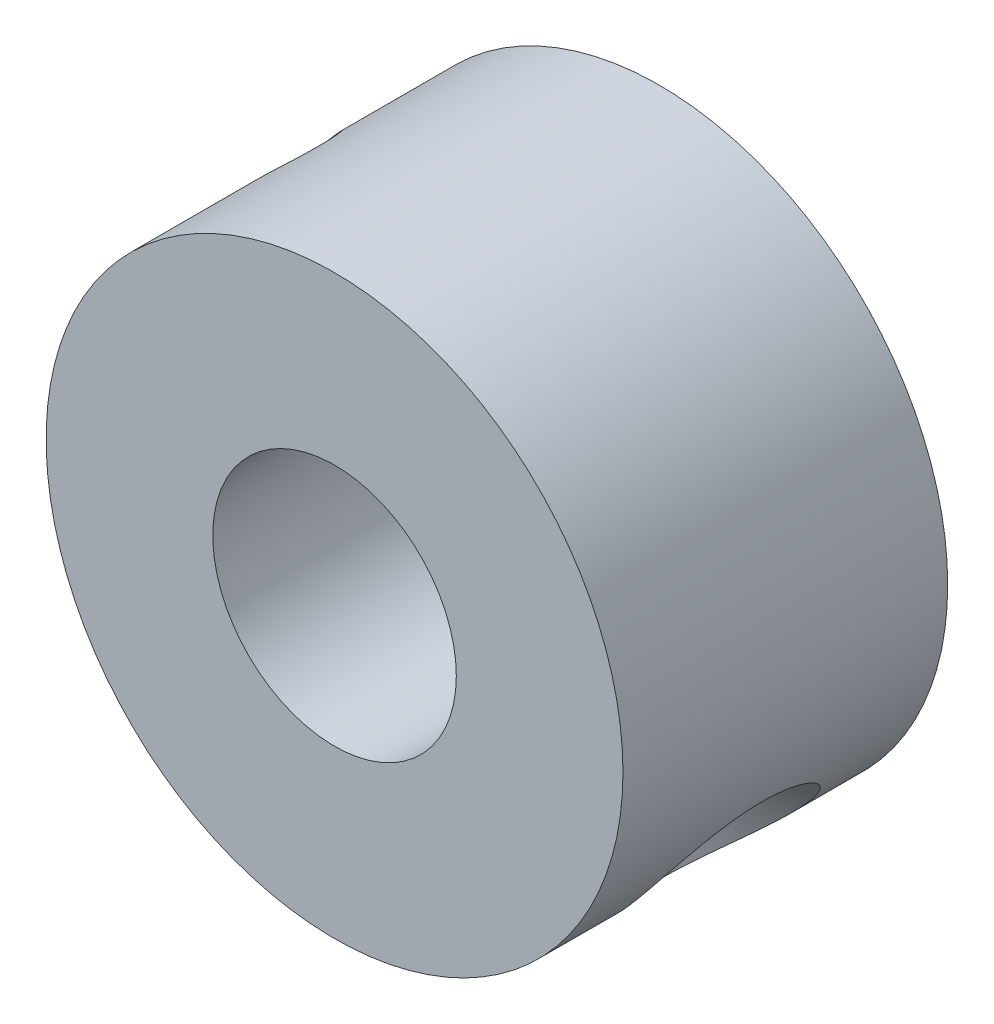
SolidWorks part; units mm, degrees
ref_plane "Front Plane" through (0, 0, 0) normal (0, 0, 1) x (1, 0, 0)
ref_plane "Top Plane" through (0, 0, 0) normal (0, 1, 0) x (1, 0, 0)
ref_plane "Right Plane" through (0, 0, 0) normal (1, 0, 0) x (0, 0, -1)
sketch "Sketch1" plane through (0, 0, 0) normal (0, 0, 1) x (1, 0, 0)
  circle A0 centre (0, 0) radius 7.1054
  circle A1 centre (0, 0) radius 3
extrude "Boss-Extrude3" add sketch "Sketch1" along normal blind 8 contours A1 | A0
sketch "Sketch2" plane through (0, 0, 8) normal (0, 0, 1) x (1, 0, 0)
  circle A0 centre (0, 0) radius 5
  circle A1 centre (0, 0) radius 3
hole_wizard "CSK for M2 Flat Head Machine Screw2" positions "3DSketch4" profile "Sketch6" countersink size "M2" standard "ANSI Metric" end condition through all
sketch3d "3DSketch4"
  point P0 (5.372, -4.6507, 3.8937)
sketch "Sketch6" plane through (5.372, -4.6507, 3.8937) normal (0, 0, 1) x (0.6545, 0.756, 0)
  line L0 (0, 0) -> (0, 17.1281)
  line L1 (0, 17.1281) -> (1.2, 17.1281)
  line L2 (1.2, 17.1281) -> (1.2, 1)
  line L3 (1.2, 1) -> (2.2, 0)
  line L5 (2.2, 0) -> (0, 0)
  line L6 (-1.2, 1) -> (-2.2, 0) construction
  line L11 (0, -6.35) -> (0, 107.95) construction
  dimension "Thru Hole Dia." = 2.4
  dimension "Thru Hole Depth" = 17.1281
  dimension "Near C'Sink Dia." = 4.4
  dimension "Near C'Sink Angle" = 90
